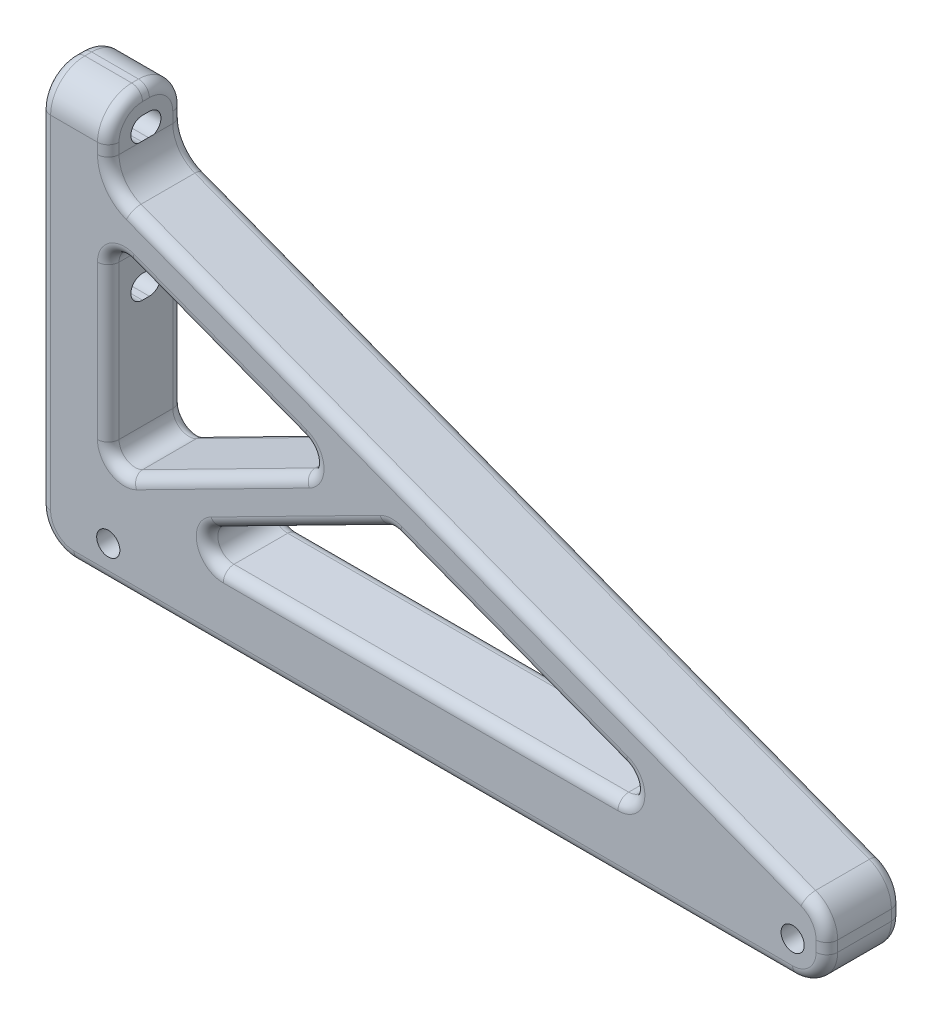
SolidWorks part; units mm, degrees
ref_plane "Front Plane" through (0, 0, 0) normal (0, 0, 1) x (1, 0, 0)
ref_plane "Top Plane" through (0, 0, 0) normal (0, 1, 0) x (1, 0, 0)
ref_plane "Right Plane" through (0, 0, 0) normal (1, 0, 0) x (0, 0, -1)
sketch "Sketch1" plane through (0, 0, 0) normal (0, 0, 1) x (1, 0, 0)
  line L0 (-12.7, 57.15) -> (-12.7, -6.35)
  line L1 (-12.7, -6.35) -> (133.35, -6.35)
  line L2 (133.35, -6.35) -> (133.35, 6.35)
  line L3 (133.35, 6.35) -> (0, 57.15)
  line L4 (0, 57.15) -> (-12.7, 57.15)
  line L5 (0, 48.5892) -> (0, 6.35)
  line L6 (0, 6.35) -> (110.8778, 6.35)
  line L7 (110.8778, 6.35) -> (0, 48.5892)
  line L8 (0, 6.35) -> (47.472, 30.5046) construction
  line L9 (8.8205, 6.35) -> (52.516, 28.5831)
  line L10 (0, 10.838) -> (42.428, 32.4261)
  line L12 (-12.7, 57.15) -> (0, 57.15)
  line L13 (-12.7, 57.15) -> (-12.7, 69.85)
  line L14 (-12.7, 69.85) -> (0, 69.85)
  line L15 (0, 57.15) -> (0, 69.85)
  circle A0 centre (0, 0) radius 2.15
  circle A1 centre (127, 0) radius 2.15
  dimension "D1" = 4.3
  dimension "D2" = 127
  dimension "D3" = 6.35
  dimension "D4" = 12.7
  dimension "D5" = 6.35
  dimension "D6" = 12.7
  dimension "D7" = 63.5
  dimension "D8" = 12.7
  dimension "D9" = 12.7
  dimension "D10" = 8
  dimension "D11" = 8
  dimension "D12" = 12.7
  dimension "D13" = 50.8
extrude "Boss-Extrude1" add sketch "Sketch1" along normal blind 13.97
fillet "Fillet1" radius 3 6 edges at (110.8778, 6.35, 6.985) (52.516, 28.5831, 6.985) (8.8205, 6.35, 6.985) (0, 10.838, 6.985) (42.428, 32.4261, 6.985) (0, 48.5892, 6.985)
fillet "Fillet2" radius 6.35 6 edges at (133.35, 6.35, 6.985) (133.35, -6.35, 6.985) (-12.7, -6.35, 6.985) (0, 57.15, 6.985) (-6.35, 69.85, 0) (-6.35, 69.85, 13.97)
sketch "Sketch2" plane through (0, 0, 0) normal (1, 0, 0) x (0, 0, -1)
  line L1 (-7.62, 63.5) -> (-6.35, 63.5) construction
  line L2 (-7.62, 65.65) -> (-6.35, 65.65)
  line L3 (-7.62, 61.35) -> (-6.35, 61.35)
  line L4 (0, 61.5261) -> (0, 63.5) construction
  line L5 (-13.97, 61.5261) -> (-13.97, 55.5921) construction
  line L6 (-7.62, 69.85) -> (-6.35, 69.85) construction
  line L7 (-7.62, 35.95) -> (-6.35, 35.95)
  line L8 (-7.62, 40.25) -> (-6.35, 40.25)
  line L9 (-7.62, 38.1) -> (-6.35, 38.1) construction
  arc A1 (-7.62, 65.65) -> (-7.62, 61.35) centre (-7.62, 63.5) ccw
  arc A2 (-6.35, 61.35) -> (-6.35, 65.65) centre (-6.35, 63.5) ccw
  arc A3 (-7.62, 40.25) -> (-7.62, 35.95) centre (-7.62, 38.1) ccw
  arc A4 (-6.35, 35.95) -> (-6.35, 40.25) centre (-6.35, 38.1) ccw
  point P2 (-6.985, 63.5)
  point P16 (-6.985, 38.1)
  dimension "D1" = 2.15
  dimension "D2" = 6.35
  dimension "D3" = 6.35
  dimension "D4" = 6.35
  dimension "D6" = 25.4
  dimension "D5" = 2
extrude "Cut-Extrude1" cut sketch "Sketch2" against normal through all
fillet "Fillet3" radius 2 48 edges at (1.4318, 13.173, 13.97) (1.4318, 13.173, 0) (0, 29.9832, 13.97) (0, 29.9832, 0) (1.2976, 46.7062, 13.97) (1.2976, 46.7062, 0) (20.0864, 40.9372, 13.97) (20.0864, 40.9372, 0) (38.0326, 32.1914, 13.97) (38.0326, 32.1914, 0) (97.5262, 8.807, 13.97) (97.5262, 8.807, 0) (57.9538, 6.35, 13.97) (57.9538, 6.35, 0) (18.4146, 8.6505, 13.97) (18.4146, 8.6505, 0) (35.651, 20.0018, 0) (35.651, 20.0018, 13.97) (52.531, 28.3018, 13.97) (52.531, 28.3018, 0) (74.7013, 20.1315, 0) (74.7013, 20.1315, 13.97) (20.3789, 21.2072, 0) (20.3789, 21.2072, 13.97) (132.2286, 5.5772, 13.97) (132.2286, 5.5772, 0) (133.35, 0.9869, 13.97) (133.35, 0.9869, 0) (131.4901, -4.4901, 13.97) (131.4901, -4.4901, 0) (60.325, -6.35, 0) (60.325, -6.35, 13.97) (-10.8401, -4.4901, 13.97) (-10.8401, -4.4901, 0) (-12.7, 31.75, 13.97) (-12.7, 67.9901, 12.1101) (-12.7, 69.85, 6.985) (-12.7, 67.9901, 1.8599) (-12.7, 31.75, 0) (66.675, 31.75, 0) (66.675, 31.75, 13.97) (1.1214, 57.9228, 13.97) (1.1214, 57.9228, 0) (0, 62.5131, 0) (0, 67.9901, 1.8599) (0, 69.85, 6.985) (0, 67.9901, 12.1101) (0, 62.5131, 13.97)
sketch "Sketch3" plane through (0, 0, 13.97) normal (0, 0, 1) x (1, 0, 0)
  line L1 (0, 0) -> (127, 0) construction
  line L3 (10.3886, 2.3114) -> (15.0114, 2.3114)
  line L4 (10.3886, 2.3114) -> (10.3886, -2.3114)
  line L5 (10.3886, -2.3114) -> (15.0114, -2.3114)
  line L6 (15.0114, 2.3114) -> (15.0114, -2.3114)
  line L7 (10.3886, 2.3114) -> (15.0114, -2.3114) construction
  line L8 (10.3886, -2.3114) -> (15.0114, 2.3114) construction
  line L9 (111.9886, 2.3114) -> (116.6114, 2.3114)
  line L10 (111.9886, 2.3114) -> (111.9886, -2.3114)
  line L11 (111.9886, -2.3114) -> (116.6114, -2.3114)
  line L12 (116.6114, 2.3114) -> (116.6114, -2.3114)
  line L13 (111.9886, 2.3114) -> (116.6114, -2.3114) construction
  line L14 (111.9886, -2.3114) -> (116.6114, 2.3114) construction
  point P0 (12.7, 0)
  point P9 (114.3, 0)
  point P14 (116.6114, 0)
  dimension "D1" = 4.6228
  dimension "D2" = 12.7
  dimension "D3" = 4.6228
  dimension "D4" = 12.7
extrude "Boss-Extrude2" add sketch "Sketch3" against normal blind 2 from surface at -13.97 starting at face at (13.4439, 30.7222, 0)
fillet "Fillet4" radius 0.508 16 edges at (114.3, -2.3114, -2) (111.9886, 0, -2) (114.3, 2.3114, -2) (116.6114, 0, -2) (12.7, -2.3114, -2) (10.3886, 0, -2) (12.7, 2.3114, -2) (15.0114, 0, -2) (116.6114, 2.3114, -1) (116.6114, -2.3114, -1) (111.9886, -2.3114, -1) (111.9886, 2.3114, -1) (10.3886, -2.3114, -1) (15.0114, -2.3114, -1) (10.3886, 2.3114, -1) (15.0114, 2.3114, -1)
